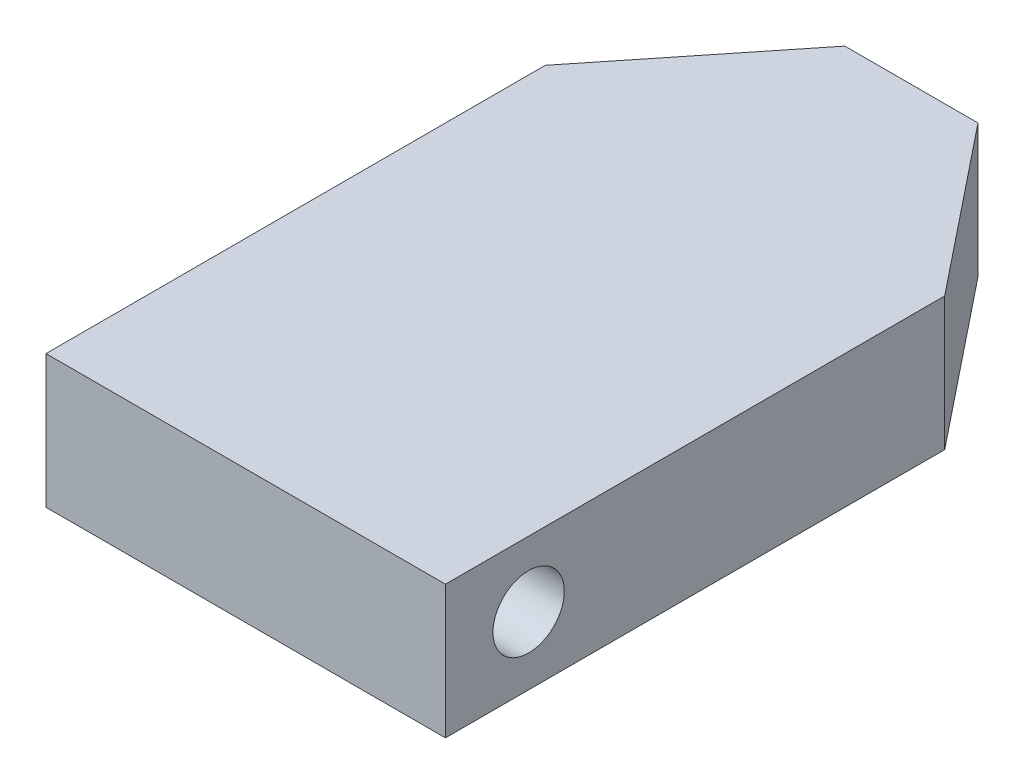
SolidWorks part; units mm, degrees
ref_plane "Front Plane" through (0, 0, 0) normal (0, 0, 1) x (1, 0, 0)
ref_plane "Top Plane" through (0, 0, 0) normal (0, 1, 0) x (1, 0, 0)
ref_plane "Right Plane" through (0, 0, 0) normal (1, 0, 0) x (0, 0, -1)
sketch "Sketch1" plane through (0, 0, 0) normal (0, 1, 0) x (1, 0, 0)
  line L0 (-101.9008, 53.4298) -> (-101.9008, -96.5702)
  line L1 (-101.9008, -96.5702) -> (18.0992, -96.5702)
  line L2 (18.0992, -96.5702) -> (18.0992, 53.4298)
  line L4 (-41.9008, 103.4298) -> (-61.9008, 103.4298)
  line L5 (-41.9008, 103.4298) -> (-21.9008, 103.4298)
  line L6 (-101.9008, 53.4298) -> (-61.9008, 103.4298)
  line L7 (-21.9008, 103.4298) -> (18.0992, 53.4298)
  dimension "D1" = 150
  dimension "D2" = 120
  dimension "D4" = 20
  dimension "D5" = 20
extrude "Boss-Extrude4" add sketch "Sketch1" along normal blind 40 contours L6 L4 L5 L7 L2 L1 L0
sketch "Sketch5" plane through (-101.9008, 0, 0) normal (-1, 0, 0) x (0, 0, 1)
  circle A1 centre (71.5726, 20.3233) radius 10.72
extrude "Cut-Extrude1" cut sketch "Sketch5" against normal blind 120
